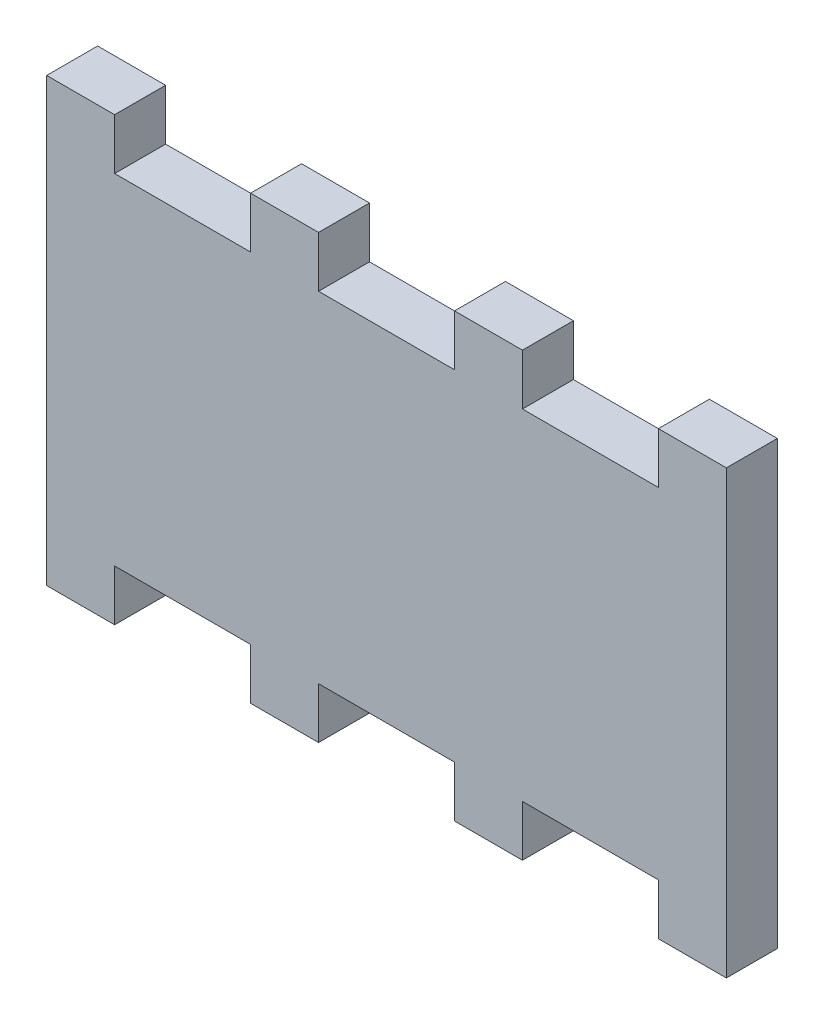
SolidWorks part; units mm, degrees
ref_plane "Plan de face" through (0, 0, 0) normal (0, 0, 1) x (1, 0, 0)
ref_plane "Plan de dessus" through (0, 0, 0) normal (0, 1, 0) x (1, 0, 0)
ref_plane "Plan de droite" through (0, 0, 0) normal (1, 0, 0) x (0, 0, -1)
sketch "Esquisse1" plane through (0, 0, 0) normal (0, 0, 1) x (1, 0, 0)
  line L0 (0, 20) -> (80, 20) construction
  line L1 (0, 0) -> (80, 0)
  line L2 (0, 0) -> (0, 40)
  line L3 (0, 40) -> (80, 40)
  line L4 (80, 0) -> (80, 40)
  line L5 (0, 40) -> (8, 40)
  line L6 (0, 40) -> (0, 46)
  line L7 (0, 46) -> (8, 46)
  line L8 (8, 40) -> (8, 46)
  line L9 (24, 40) -> (32, 40)
  line L10 (24, 40) -> (24, 46)
  line L11 (24, 46) -> (32, 46)
  line L12 (32, 40) -> (32, 46)
  line L13 (48, 40) -> (56, 40)
  line L14 (48, 40) -> (48, 46)
  line L15 (48, 46) -> (56, 46)
  line L16 (56, 40) -> (56, 46)
  line L17 (72, 40) -> (80, 40)
  line L18 (72, 40) -> (72, 46)
  line L19 (72, 46) -> (80, 46)
  line L20 (80, 40) -> (80, 46)
  line L22 (0, -6) -> (80, -6)
  line L24 (0, -6) -> (8, -6)
  line L25 (0, -6) -> (0, 0)
  line L26 (0, 0) -> (8, 0)
  line L27 (8, -6) -> (8, 0)
  line L28 (24, -6) -> (32, -6)
  line L29 (24, -6) -> (24, 0)
  line L30 (24, 0) -> (32, 0)
  line L31 (32, -6) -> (32, 0)
  line L32 (48, -6) -> (56, -6)
  line L33 (48, -6) -> (48, 0)
  line L34 (48, 0) -> (56, 0)
  line L35 (56, -6) -> (56, 0)
  line L36 (72, -6) -> (80, -6)
  line L37 (72, -6) -> (72, 0)
  line L38 (72, 0) -> (80, 0)
  line L39 (80, -6) -> (80, 0)
  dimension "D1" = 80
  dimension "D2" = 40
  dimension "D3" = 8
  dimension "D4" = 16
  dimension "D5" = 8
  dimension "D6" = 16
  dimension "D7" = 8
  dimension "D8" = 8
  dimension "D9" = 16
  dimension "D10" = 6
  dimension "D12" = 8
  dimension "D13" = 16
  dimension "D14" = 8
  dimension "D15" = 16
  dimension "D16" = 8
  dimension "D17" = 8
  dimension "D18" = 16
  dimension "D19" = 6
extrude "Boss.-Extru.1" add sketch "Esquisse1" along normal blind 6 contours L22 L27 L1 L25 | L22 L31 L1 L29 | L22 L35 L1 L33 | L0 L2 L1 L4 | L2 L0 L4 L3 | L3 L20 L19 L18 | L3 L16 L15 L14 | L3 L12 L11 L10 | L3 L8 L7 L6 | L36 L37 L38 L39
